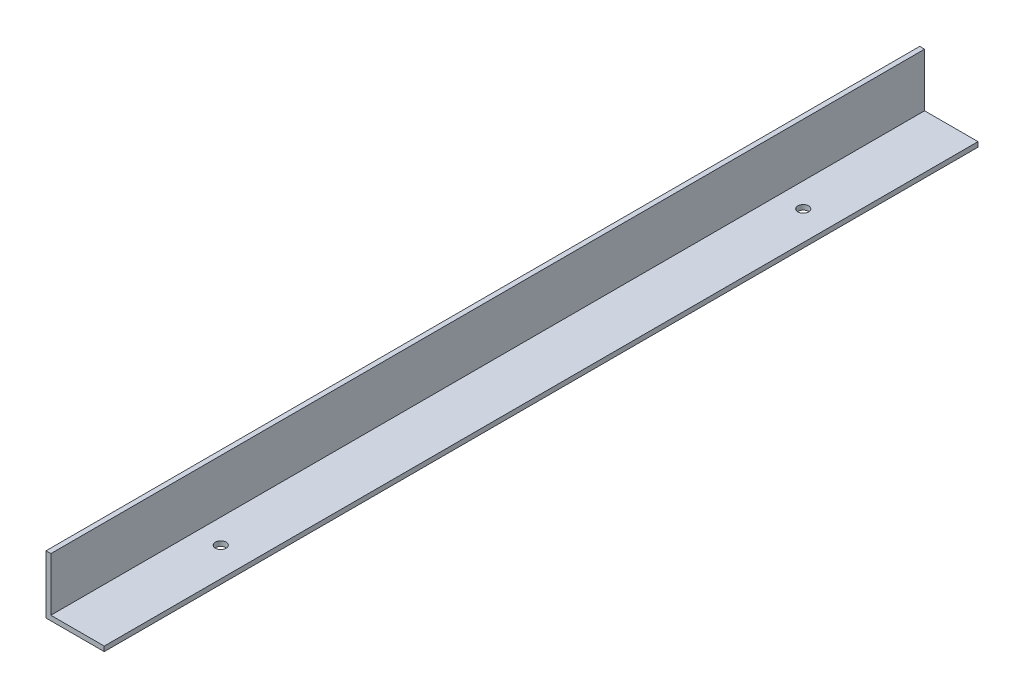
SolidWorks part; units mm, degrees
ref_plane "前视基准面" through (0, 0, 0) normal (0, 0, 1) x (1, 0, 0)
ref_plane "上视基准面" through (0, 0, 0) normal (0, 1, 0) x (1, 0, 0)
ref_plane "右视基准面" through (0, 0, 0) normal (1, 0, 0) x (0, 0, -1)
sketch "草图1" plane through (0, 0, 0) normal (0, 0, 1) x (1, 0, 0)
  line L0 (0, 0) -> (120, 0)
  line L1 (120, 0) -> (120, 10)
  line L2 (120, 10) -> (10, 10)
  line L3 (10, 10) -> (10, 120)
  line L4 (10, 120) -> (0, 120)
  line L5 (0, 120) -> (0, 0)
  dimension "D1" = 10
  dimension "D2" = 10
  dimension "D3" = 120
  dimension "D4" = 120
extrude "凸台-拉伸1" add sketch "草图1" along normal blind 1800
sketch "草图2" plane through (0, 0, 0) normal (0, -1, 0) x (-1, 0, 0)
  line L0 (-60, -1800) -> (-60, 48200) construction
  line L1 (0, -1800) -> (-120, -1800) construction
  line L2 (0, 0) -> (-120, 0) construction
  line L3 (0, -900) -> (-50000, -900) construction
  line L4 (0, -1800) -> (0, 0) construction
  line L5 (-120, -1800) -> (-120, 0) construction
  circle A0 centre (-60, -1500) radius 11
  circle A1 centre (-60, -300) radius 11
  point P4 (-60, -1800)
  point P7 (-60, 0)
  point P12 (0, -900)
  point P15 (-120, -900)
  dimension "D1" = 22
  dimension "D2" = 22
  dimension "D3" = 1200
extrude "切除-拉伸1" cut sketch "草图2" against normal through all
